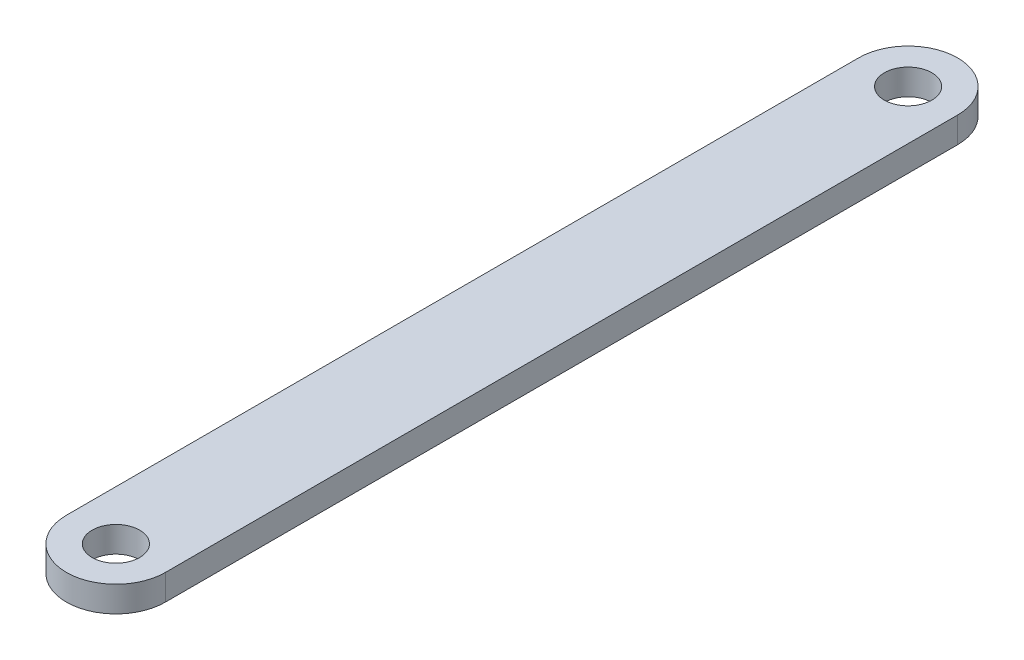
SolidWorks part; units mm, degrees
ref_plane "Front Plane" through (0, 0, 0) normal (0, 0, 1) x (1, 0, 0)
ref_plane "Top Plane" through (0, 0, 0) normal (0, 1, 0) x (1, 0, 0)
ref_plane "Right Plane" through (0, 0, 0) normal (1, 0, 0) x (0, 0, -1)
sketch "Sketch1" plane through (0, 0, 0) normal (0, 1, 0) x (1, 0, 0)
  line L0 (0, 100) -> (0, -100) construction
  line L1 (12.5, 100) -> (12.5, -100)
  line L2 (-12.5, 100) -> (-12.5, -100)
  arc A0 (12.5, 100) -> (-12.5, 100) centre (0, 100) ccw
  arc A1 (-12.5, -100) -> (12.5, -100) centre (0, -100) ccw
  circle A2 centre (0, 100) radius 6
  circle A3 centre (0, -100) radius 6
  point P2 (0, 0)
  dimension "D1" = 12.5
  dimension "D3" = 12
  dimension "D2" = 200
extrude "Boss-Extrude1" add sketch "Sketch1" along normal mid plane 6.5
